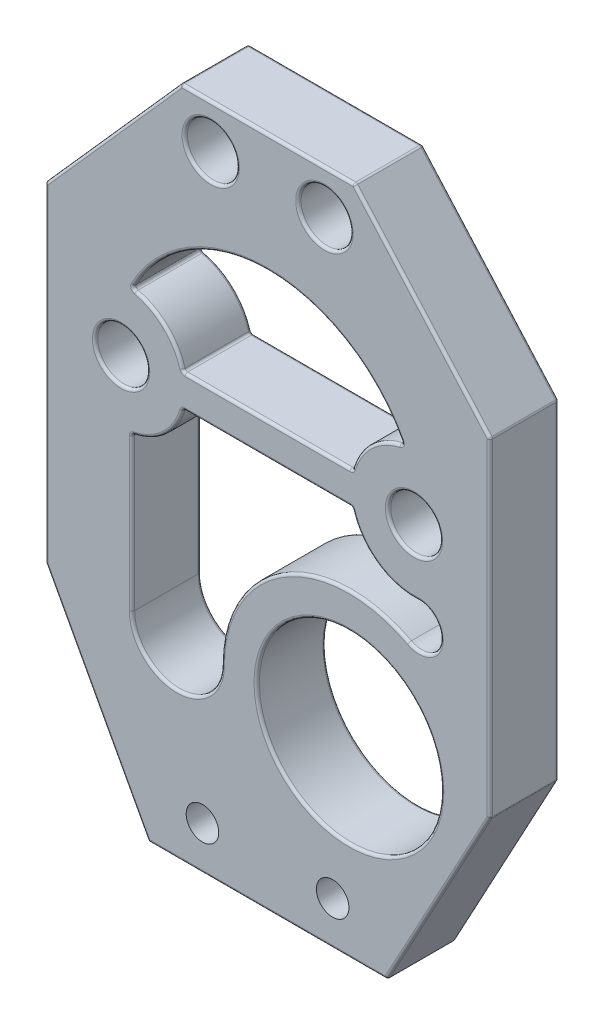
SolidWorks part; units mm, degrees
material "AISI 304"
ref_plane "Plano frontal" through (0, 0, 0) normal (0, 0, 1) x (1, 0, 0)
ref_plane "Plano superior" through (0, 0, 0) normal (0, 1, 0) x (1, 0, 0)
ref_plane "Plano direito" through (0, 0, 0) normal (1, 0, 0) x (0, 0, -1)
sketch "Esboço1" plane through (0, 0, 0) normal (0, 0, 1) x (1, 0, 0)
  line L0 (0, 89.497) -> (0, -48.9301) construction
  line L1 (-7.99, 62) -> (7.99, 62)
  line L2 (-7.99, 62) -> (-20.5, 47.9)
  line L3 (-20.5, 47.9) -> (-20.5, 17.6)
  line L4 (-20.5, 17.6) -> (-11, 0)
  line L5 (-11, 0) -> (11, 0)
  line L6 (20.5, 17.6) -> (11, 0)
  line L7 (20.5, 47.9) -> (20.5, 17.6)
  line L8 (7.99, 62) -> (20.5, 47.9)
  line L9 (-7.7939, 39.1) -> (7.7939, 39.1)
  line L10 (-12.4954, 31.7862) -> (-12.4954, 17.6)
  line L11 (-13.5, 37.6) -> (13.5, 37.6) construction
  line L12 (-7.7939, 36.1) -> (7.7939, 36.1)
  circle A0 centre (5.24, 58) radius 2.395
  circle A1 centre (-5.24, 58) radius 2.395
  circle A2 centre (6, 4) radius 1.5
  circle A3 centre (-6, 4) radius 1.5
  circle A4 centre (7.5, 17.6) radius 8.5
  circle A5 centre (13.5, 37.6) radius 2.395
  circle A6 centre (-13.5, 37.6) radius 2.395
  arc A7 (-12.4954, 31.7862) -> (-7.7939, 36.1) centre (-13.5, 37.6) ccw
  arc A8 (12.4954, 43.4138) -> (7.7939, 39.1) centre (13.5, 37.6) ccw
  arc A9 (-12.4954, 43.4138) -> (12.4954, 43.4138) centre (0, 37.1) cw
  arc A10 (-12.4954, 17.6) -> (-4.2246, 17.6) centre (-8.36, 17.6) ccw
  arc A11 (-4.2246, 17.6) -> (13.0125, 27.9478) centre (7.5, 17.6) cw
  arc A13 (13.0125, 27.9478) -> (13.8382, 31.7097) centre (13.9529, 29.713) ccw
  arc A14 (7.7939, 36.1) -> (13.8382, 31.7097) centre (13.5, 37.6) ccw
  arc A15 (-7.7939, 39.1) -> (-12.4954, 43.4138) centre (-13.5, 37.6) ccw
  point P6 (0, 62)
  point P13 (0, 0)
  point P16 (0, 62)
  dimension "D7" = 4.79
  dimension "D8" = 4
  dimension "D9" = 15.26
  dimension "D10" = 3
  dimension "D11" = 4
  dimension "D12" = 5
  dimension "D13" = 17
  dimension "D14" = 13
  dimension "D15" = 17.6
  dimension "D16" = 4.79
  dimension "D17" = 24.4
  dimension "D18" = 7
  dimension "D19" = 11.8
  dimension "D22" = 14
  dimension "D24" = 2
  dimension "D1" = 11
  dimension "D2" = 12.51
  dimension "D3" = 30.3
  dimension "D4" = 14.1
  dimension "D5" = 17.6
  dimension "D6" = 9.5
  dimension "D20" = 10.9
  dimension "D21" = 12
  dimension "D23" = 12.14
extrude "Ressalto-extrusão1" add sketch "Esboço1" along normal blind 6.35
fillet "Filete1" radius 0.25 63 edges at (-7.99, 62, 3.175) (-20.5, 47.9, 3.175) (7.99, 62, 3.175) (20.5, 47.9, 3.175) (11, 0, 3.175) (20.5, 17.6, 3.175) (0, 62, 6.35) (14.245, 54.95, 6.35) (20.5, 32.75, 6.35) (15.75, 8.8, 6.35) (0, 0, 6.35) (-20.5, 32.75, 6.35) (-14.245, 54.95, 6.35) (0, 36.1, 0) (10.0327, 32.8264, 0) (15.9064, 29.2842, 0) (1.4654, 27.6523, 0) (-8.36, 13.4646, 0) (-12.4954, 24.6931, 0) (-9.5112, 33.2527, 0) (-11.105, 37.6, 0) (15.895, 37.6, 0) (16, 17.6, 0) (7.635, 58, 0) (-2.845, 58, 0) (-20.5, 32.75, 0) (0, 0, 0) (15.75, 8.8, 0) (20.5, 32.75, 0) (14.245, 54.95, 0) (0, 62, 0) (-14.245, 54.95, 0) (0, 51.1, 0) (9.5112, 41.9473, 0) (0, 39.1, 0) (-9.5112, 41.9473, 0) (-20.5, 17.6, 3.175) (-15.75, 8.8, 6.35) (-11, 0, 3.175) (-15.75, 8.8, 0) (-12.4954, 43.4138, 3.175) (9.5112, 41.9473, 6.35) (-9.5112, 41.9473, 6.35) (-9.5112, 33.2527, 6.35) (10.0327, 32.8264, 6.35) (15.9064, 29.2842, 6.35) (1.4654, 27.6523, 6.35) (0, 51.1, 6.35) (12.4954, 43.4138, 3.175) (-12.4954, 24.6931, 6.35) (-12.4954, 31.7862, 3.175) (7.7939, 39.1, 3.175) (0, 39.1, 6.35) (-7.7939, 39.1, 3.175) (-11.105, 37.6, 6.35) (-2.845, 58, 6.35) (7.635, 58, 6.35) (15.895, 37.6, 6.35) (-7.7939, 36.1, 3.175) (0, 36.1, 6.35) (7.7939, 36.1, 3.175) (-8.36, 13.4646, 6.35) (16, 17.6, 6.35)
